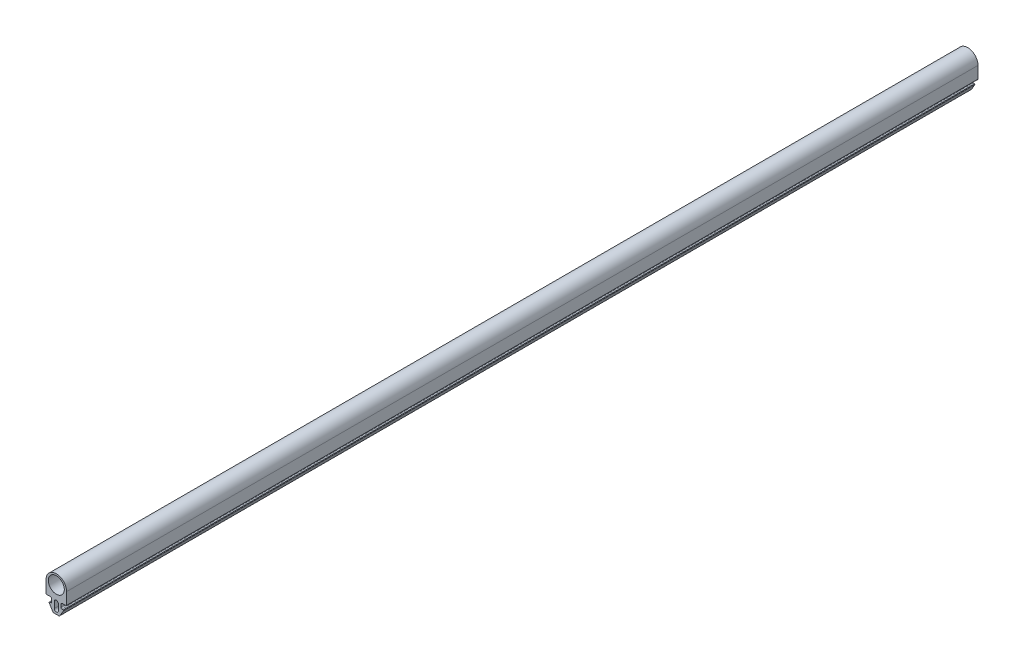
SolidWorks part; units mm, degrees
ref_plane "Plan de face" through (0, 0, 0) normal (0, 0, 1) x (1, 0, 0)
ref_plane "Plan de dessus" through (0, 0, 0) normal (0, 1, 0) x (1, 0, 0)
ref_plane "Plan de droite" through (0, 0, 0) normal (1, 0, 0) x (0, 0, -1)
ref_plane "Plan1" through (0, 0, 20) normal (0, 0, 1) x (1, 0, 0)
sketch "Esquisse1" plane through (0, 0, 20) normal (0, 0, 1) x (1, 0, 0)
  line L0 (-9, 10.8646) -> (-9, 0.5239)
  line L1 (-8.4781, 0) -> (-5.5, 0)
  line L2 (-4, -1.5) -> (-4, -3.5)
  line L3 (-5, -4.5) -> (-6.016, -4.5)
  line L4 (-6.1742, -5.1677) -> (-3.44, -9.9034)
  line L5 (-1.708, -10.9034) -> (1.708, -10.9034)
  line L6 (3.44, -9.9034) -> (6.1742, -5.1677)
  line L7 (6.016, -4.5) -> (5, -4.5)
  line L8 (4, -3.5) -> (4, -1.5)
  line L9 (5.5, 0) -> (8.4781, 0)
  line L10 (9, 0.5239) -> (9, 10.8646)
  line L11 (1.75, -1.9534) -> (1.75, -7.3515)
  line L12 (-1.75, -7.3515) -> (-1.75, -1.9534)
  arc A0 (9, 10.8646) -> (-9, 10.8646) centre (0, 10.8646) ccw
  arc A1 (-9, 0.5239) -> (-8.4781, 0) centre (-8.5006, 0.4995) ccw
  arc A2 (-5.5, 0) -> (-4, -1.5) centre (-5.5, -1.5) cw
  arc A3 (-4, -3.5) -> (-5, -4.5) centre (-5, -3.5) cw
  arc A4 (-6.016, -4.5) -> (-6.1742, -5.1677) centre (-5.7412, -4.9177) ccw
  arc A5 (-3.44, -9.9034) -> (-1.708, -10.9034) centre (-1.708, -8.9034) ccw
  arc A6 (1.708, -10.9034) -> (3.44, -9.9034) centre (1.708, -8.9034) ccw
  arc A7 (6.1742, -5.1677) -> (6.016, -4.5) centre (5.7412, -4.9177) ccw
  arc A8 (5, -4.5) -> (4, -3.5) centre (5, -3.5) cw
  arc A9 (4, -1.5) -> (5.5, 0) centre (5.5, -1.5) cw
  arc A10 (8.4781, 0) -> (9, 0.5239) centre (8.5006, 0.4995) ccw
  arc A11 (-1.75, -1.9534) -> (1.75, -1.9534) centre (0, -1.9534) cw
  arc A12 (1.75, -7.3515) -> (-1.75, -7.3515) centre (0, -7.3515) cw
  circle A13 centre (0, 11.36) radius 7
extrude "Boss.-Extru.1" add sketch "Esquisse1" against normal blind 796
